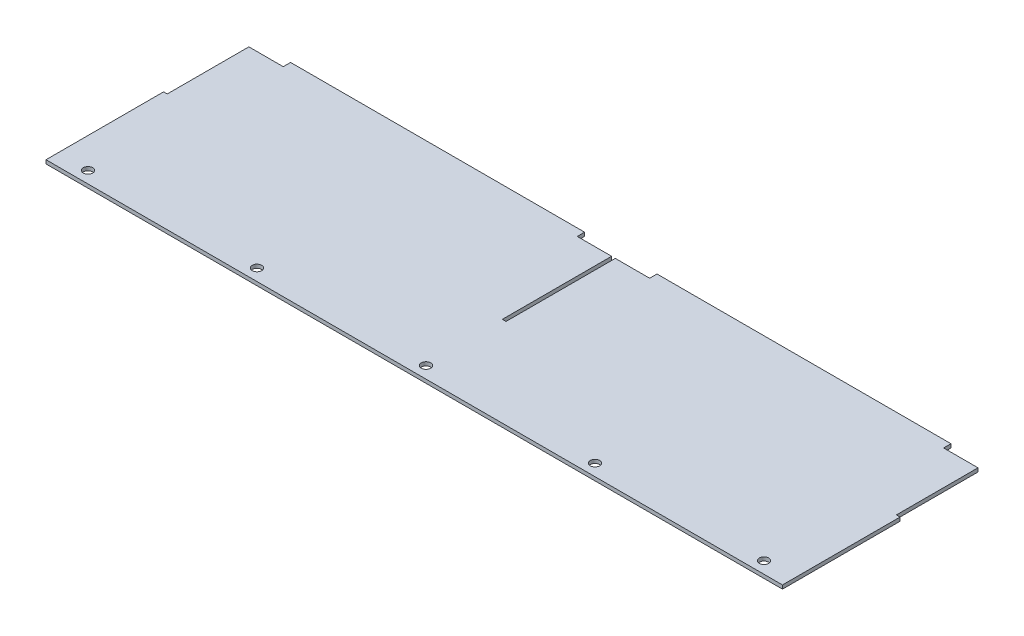
SolidWorks part; units mm, degrees
material "6061-T6 (SS)"
ref_plane "X-Y Datum" through (0, 0, 0) normal (0, 0, 1) x (1, 0, 0)
ref_plane "X-Z Datum" through (0, 0, 0) normal (0, 1, 0) x (1, 0, 0)
ref_plane "Y-Z Datum" through (0, 0, 0) normal (1, 0, 0) x (0, 0, -1)
sketch "Sketch1" plane through (0, 0, 0) normal (0, 1, 0) x (1, 0, 0)
  line L1 (0, 0) -> (636.2598, 0)
  line L2 (0, 0) -> (0, 172.0926)
  line L3 (0, 172.0926) -> (636.2598, 172.0926)
  line L4 (636.2598, 0) -> (636.2598, 172.0926)
extrude "Boss-Extrude1" add sketch "Sketch1" along normal blind 3.175 contours L3 L4 L1 L2
sketch "Sketch2" plane through (0, 0, -172.0926) normal (0, 0, -1) x (-1, 0, 0)
  line L3 (-319.7174, 3.175) -> (-316.5424, 3.175) construction
  line L4 (-319.7174, 3.175) -> (-316.5424, 3.175)
  line L5 (-319.7174, 3.175) -> (-319.7174, 0)
  line L6 (-319.7174, 0) -> (-316.5424, 0)
  line L7 (-316.5424, 3.175) -> (-316.5424, 0)
  line L9 (-319.7174, 0) -> (-316.5424, 0) construction
extrude "Cut-Extrude1" cut sketch "Sketch2" against normal blind 94.3661
sketch "Sketch3" plane through (0, 0, -172.0926) normal (0, 0, 1) x (1, 0, 0)
  line L0 (0, 0) -> (636.2598, 0) construction
  line L1 (0, 3.175) -> (3.175, 3.175)
  line L2 (0, 3.175) -> (0, 0)
  line L3 (0, 0) -> (3.175, 0)
  line L4 (3.175, 3.175) -> (3.175, 0)
  line L6 (636.2598, 3.175) -> (633.0848, 3.175)
  line L7 (636.2598, 3.175) -> (636.2598, 0)
  line L8 (636.2598, 0) -> (633.0848, 0)
  line L9 (633.0848, 3.175) -> (633.0848, 0)
extrude "Cut-Extrude5" cut sketch "Sketch3" along normal blind 70.4926
sketch "Sketch4" plane through (0, 3.175, 0) normal (0, 1, 0) x (1, 0, 0)
  line L0 (636.2598, 0) -> (636.2598, 101.6) construction
  line L1 (0, 0) -> (636.2598, 0)
  line L2 (0, 0) -> (0, 24.3942)
  line L3 (0, 24.3942) -> (636.2598, 24.3942)
  line L4 (636.2598, 0) -> (636.2598, 24.3942)
extrude "Cut-Extrude6" cut sketch "Sketch4" against normal through all
sketch "Sketch6" plane through (0, 3.175, 0) normal (0, 1, 0) x (1, 0, 0)
  line L1 (0, 24.3942) -> (636.2598, 24.3942)
  line L2 (0, 24.3942) -> (0, 0)
  line L3 (0, 0) -> (636.2598, 0)
  line L4 (636.2598, 24.3942) -> (636.2598, 0)
extrude "Boss-Extrude2" add sketch "Sketch6" against normal through all
sketch "Sketch7" plane through (0, 0, -172.0926) normal (0, 0, -1) x (-1, 0, 0)
  line L0 (-319.7174, 3.175) -> (-633.0848, 3.175) construction
  line L1 (-603.4011, 3.175) -> (-349.4011, 3.175)
  line L2 (-603.4011, 3.175) -> (-603.4011, 0)
  line L3 (-603.4011, 0) -> (-349.4011, 0)
  line L4 (-349.4011, 3.175) -> (-349.4011, 0)
  line L5 (-319.7174, 0) -> (-633.0848, 0) construction
  line L6 (-633.0848, 3.175) -> (-633.0848, 0) construction
  line L7 (-318.1299, 3.175) -> (-318.1299, 7.3465) construction
  line L9 (-32.8587, 0) -> (-286.8587, 0)
  line L10 (-286.8587, 3.175) -> (-286.8587, 0)
  line L11 (-32.8587, 3.175) -> (-286.8587, 3.175)
  line L12 (-32.8587, 3.175) -> (-32.8587, 0)
  dimension "D1" = 254
  dimension "D2" = 29.6837
extrude "Boss-Extrude3" add sketch "Sketch7" along normal blind 6.35
sketch "Sketch8" plane through (0, 3.175, 0) normal (0, 1, 0) x (1, 0, 0)
  line L0 (0, 0) -> (8.4495, 0) construction
  line L1 (0, 0) -> (0, 6.085) construction
  line L2 (0, 6.085) -> (8.4495, 6.085) construction
  line L3 (8.4495, 0) -> (8.4495, 6.085) construction
  circle A0 centre (26.1071, 10.16) radius 4.064
  circle A1 centre (172.1185, 10.16) radius 4.064
  circle A2 centre (318.1299, 10.16) radius 4.064
  circle A3 centre (464.1413, 10.16) radius 4.064
  circle A4 centre (610.1527, 10.16) radius 4.064
  point P0 (610.1527, 10.16)
  point P1 (464.1413, 10.16)
  point P2 (318.1299, 10.16)
  point P3 (172.1185, 10.16)
  point P4 (26.1071, 10.16)
extrude "Cut-Extrude7" cut sketch "Sketch8" against normal through all
